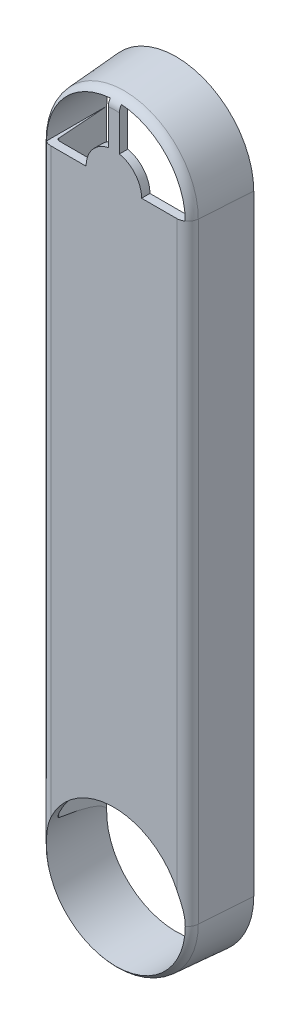
SolidWorks part; units mm, degrees
material "PA Type 6"
ref_plane "Plan de face" through (0, 0, 0) normal (0, 0, 1) x (1, 0, 0)
ref_plane "Plan de dessus" through (0, 0, 0) normal (0, 1, 0) x (1, 0, 0)
ref_plane "Plan de droite" through (0, 0, 0) normal (1, 0, 0) x (0, 0, -1)
sketch "Esquisse1" plane through (0, 0, 0) normal (0, 0, 1) x (1, 0, 0)
  line L0 (0, 0) -> (0, 90.8214) construction
  line L3 (0, 0) -> (0, 110)
  line L5 (28, 0) -> (28, 110)
  arc A0 (28, 110) -> (0, 110) centre (14, 110) ccw
  arc A1 (0, 0) -> (28, 0) centre (14, 0) ccw
  dimension "D3" = 28
  dimension "D4" = 28
  dimension "D1" = 28
  dimension "D2" = 110
extrude "Extrusion1" add sketch "Esquisse1" along normal blind 11.2 draft 4
fillet "Congé1" radius 2 4 edges at (14, -13.2168, 11.2) (0.7832, 55, 11.2) (14, 123.2168, 11.2) (27.2168, 55, 11.2)
shell "Coque1" thickness 1.5
sketch "Esquisse2" plane through (0, 0, 11.2) normal (0, 0, 1) x (1, 0, 0)
  line L0 (14, 0) -> (14, -20.2339) construction
  line L4 (14, 110) -> (14, 127.1713) construction
  line L5 (13, 122.4599) -> (13, 114.899)
  line L6 (15, 122.4599) -> (15, 114.899)
  line L7 (1.5, 110) -> (9, 110)
  line L8 (19, 110) -> (26.5, 110)
  arc A0 (17, -12.1347) -> (11, -12.1347) centre (14, 0) ccw
  arc A1 (0.6531, 0) -> (27.3469, 0) centre (14, 0) ccw construction
  arc A2 (26.5, 110) -> (15, 122.4599) centre (14, 110) ccw
  arc A3 (19, 110) -> (15, 114.899) centre (14, 110) ccw
  arc A5 (13, 122.4599) -> (1.5, 110) centre (14, 110) ccw
  arc A6 (13, 114.899) -> (9, 110) centre (14, 110) ccw
  arc A7 (11, -12.1347) -> (17, -12.1347) centre (14, 0) ccw
  point P11 (14, -8)
  dimension "D1" = 25
  dimension "D4" = 25
  dimension "D5" = 10
  dimension "D6" = 2
  dimension "D7" = 1
extrude "Enlèv. mat.-Extru.1" cut sketch "Esquisse2" against normal through all
ref_plane "Plan1" through (0, 20, 0) normal (0, 1, 0) x (-1, 0, 0)
sketch "Esquisse4" plane through (0, 20, 0) normal (0, 1, 0) x (-1, 0, 0)
  line L0 (-19, 9.7) -> (-25.3518, 9.7) construction
  line L1 (-25.8506, 9.2349) -> (-26.4963, 0) construction
  line L2 (-23, 9.7) -> (-25.3518, 9.7)
  line L3 (-25.8506, 9.2349) -> (-26.4614, 0.5)
  line L4 (-2.1494, 9.2349) -> (-1.5037, 0) construction
  line L5 (-2.6482, 9.7) -> (-9, 9.7) construction
  line L6 (-2.1494, 9.2349) -> (-1.5386, 0.5)
  line L7 (-2.6482, 9.7) -> (-5, 9.7)
  line L8 (-14, 9.3395) -> (-14, 17.3585) construction
  line L9 (-0.6531, 9.3395) -> (-27.3469, 9.3395) construction
  line L10 (-23, 9.7) -> (-23, 7)
  line L11 (-5, 9.7) -> (-5, 7)
  line L12 (-23.5, 6.5) -> (-24.5, 6.5)
  line L13 (-4.5, 6.5) -> (-3.5, 6.5)
  line L14 (-25, 6) -> (-25, 1)
  line L15 (-3, 6) -> (-3, 1)
  line L16 (-25.5, 0.5) -> (-26.4614, 0.5)
  line L17 (-2.5, 0.5) -> (-1.5386, 0.5)
  line L18 (-28, 0) -> (0, 0) construction
  arc A0 (-25.3518, 9.7) -> (-25.8506, 9.2349) centre (-25.3518, 9.2) ccw construction
  arc A1 (-25.3518, 9.7) -> (-25.8506, 9.2349) centre (-25.3518, 9.2) ccw
  arc A2 (-2.1494, 9.2349) -> (-2.6482, 9.7) centre (-2.6482, 9.2) ccw construction
  arc A3 (-2.1494, 9.2349) -> (-2.6482, 9.7) centre (-2.6482, 9.2) ccw
  arc A4 (-23, 7) -> (-23.5, 6.5) centre (-23.5, 7) cw
  arc A5 (-25, 6) -> (-24.5, 6.5) centre (-24.5, 6) cw
  arc A6 (-25.5, 0.5) -> (-25, 1) centre (-25.5, 1) ccw
  arc A7 (-4.5, 6.5) -> (-5, 7) centre (-4.5, 7) cw
  arc A8 (-3, 6) -> (-3.5, 6.5) centre (-3.5, 6) ccw
  arc A9 (-2.5, 0.5) -> (-3, 1) centre (-2.5, 1) cw
  point P28 (-23, 6.5)
  point P31 (-25, 6.5)
  point P34 (-25, 0.5)
  point P37 (-5, 6.5)
  point P40 (-3, 6.5)
  point P43 (-3, 0.5)
  dimension "D5" = 0.5
  dimension "D1" = 6
  dimension "D2" = 6.5
  dimension "D3" = 18
  dimension "D4" = 22
extrude "Extrusion2" add sketch "Esquisse4" along normal blind 1
ref_plane "Plan2" through (0, 90, 0) normal (0, 1, 0) x (-1, 0, 0)
sketch "Esquisse5" plane through (0, 90, 0) normal (0, 1, 0) x (-1, 0, 0)
  line L6 (-25.8506, 9.2349) -> (-26.4614, 0.5)
  line L7 (-26.4614, 0.5) -> (-25.5, 0.5)
  line L8 (-25, 1) -> (-25, 6)
  line L9 (-24.5, 6.5) -> (-23.5, 6.5)
  line L10 (-23, 7) -> (-23, 9.7)
  line L11 (-23, 9.7) -> (-25.3518, 9.7)
  line L12 (-25.8506, 9.2349) -> (-26.4614, 0.5)
  line L13 (-26.4614, 0.5) -> (-25.5, 0.5)
  line L14 (-25, 1) -> (-25, 6)
  line L15 (-24.5, 6.5) -> (-23.5, 6.5)
  line L16 (-23, 7) -> (-23, 9.7)
  line L17 (-23, 9.7) -> (-25.3518, 9.7)
  line L18 (-2.6482, 9.7) -> (-5, 9.7)
  line L19 (-5, 9.7) -> (-5, 7)
  line L20 (-4.5, 6.5) -> (-3.5, 6.5)
  line L21 (-3, 6) -> (-3, 1)
  line L22 (-2.5, 0.5) -> (-1.5386, 0.5)
  line L23 (-1.5386, 0.5) -> (-2.1494, 9.2349)
  line L24 (-2.6482, 9.7) -> (-5, 9.7)
  line L25 (-5, 9.7) -> (-5, 7)
  line L26 (-4.5, 6.5) -> (-3.5, 6.5)
  line L27 (-3, 6) -> (-3, 1)
  line L28 (-2.5, 0.5) -> (-1.5386, 0.5)
  line L29 (-1.5386, 0.5) -> (-2.1494, 9.2349)
  arc A4 (-25.3518, 9.7) -> (-25.8506, 9.2349) centre (-25.3518, 9.2) ccw
  arc A5 (-25.5, 0.5) -> (-25, 1) centre (-25.5, 1) ccw
  arc A6 (-24.5, 6.5) -> (-25, 6) centre (-24.5, 6) ccw
  arc A7 (-23.5, 6.5) -> (-23, 7) centre (-23.5, 7) ccw
  arc A8 (-25.3518, 9.7) -> (-25.8506, 9.2349) centre (-25.3518, 9.2) ccw
  arc A9 (-25.5, 0.5) -> (-25, 1) centre (-25.5, 1) ccw
  arc A10 (-24.5, 6.5) -> (-25, 6) centre (-24.5, 6) ccw
  arc A11 (-23.5, 6.5) -> (-23, 7) centre (-23.5, 7) ccw
  arc A12 (-2.1494, 9.2349) -> (-2.6482, 9.7) centre (-2.6482, 9.2) ccw
  arc A13 (-5, 7) -> (-4.5, 6.5) centre (-4.5, 7) ccw
  arc A14 (-3, 6) -> (-3.5, 6.5) centre (-3.5, 6) ccw
  arc A15 (-3, 1) -> (-2.5, 0.5) centre (-2.5, 1) ccw
  arc A16 (-2.1494, 9.2349) -> (-2.6482, 9.7) centre (-2.6482, 9.2) ccw
  arc A17 (-5, 7) -> (-4.5, 6.5) centre (-4.5, 7) ccw
  arc A18 (-3, 6) -> (-3.5, 6.5) centre (-3.5, 6) ccw
  arc A19 (-3, 1) -> (-2.5, 0.5) centre (-2.5, 1) ccw
  dimension "D1" = 0
  dimension "D2" = 0
extrude "Extrusion3" add sketch "Esquisse5" along normal blind 1
sketch "Esquisse6" plane through (0, 0, 0) normal (0, 0, -1) x (-1, 0, 0)
  line L0 (-14, 110) -> (-14, 125.1202) construction
  line L1 (-16.941, 122.1491) -> (-16.941, 118.8549)
  line L2 (-10.941, 122.1199) -> (-10.941, 118.8082)
  line L4 (-22.8608, 112.9468) -> (-26.1347, 113)
  line L5 (-5.1392, 112.9468) -> (-1.8653, 113)
  arc A0 (-5.6132, 113.2653) -> (-10.6283, 118.3446) centre (-14, 110) ccw
  arc A1 (-1.8653, 113) -> (-10.941, 122.1199) centre (-14, 110) ccw
  arc A2 (-17.2599, 118.3889) -> (-22.3868, 113.2653) centre (-14, 110) ccw
  arc A3 (-16.941, 122.1491) -> (-26.1347, 113) centre (-14, 110) ccw
  arc A4 (-1.5, 110) -> (-13, 122.4599) centre (-14, 110) ccw construction
  arc A5 (-22.3868, 113.2653) -> (-22.8608, 112.9468) centre (-22.8527, 113.4467) cw
  arc A6 (-16.941, 118.8549) -> (-17.2599, 118.3889) centre (-17.441, 118.8549) cw
  arc A7 (-10.941, 118.8082) -> (-10.6283, 118.3446) centre (-10.441, 118.8082) ccw
  arc A8 (-5.1392, 112.9468) -> (-5.6132, 113.2653) centre (-5.1473, 113.4467) cw
  point P18 (-16.941, 118.5059)
  dimension "D2" = 9
  dimension "D3" = 0.5
  dimension "D1" = 6
extrude "Extrusion4" add sketch "Esquisse6" along normal blind 1
